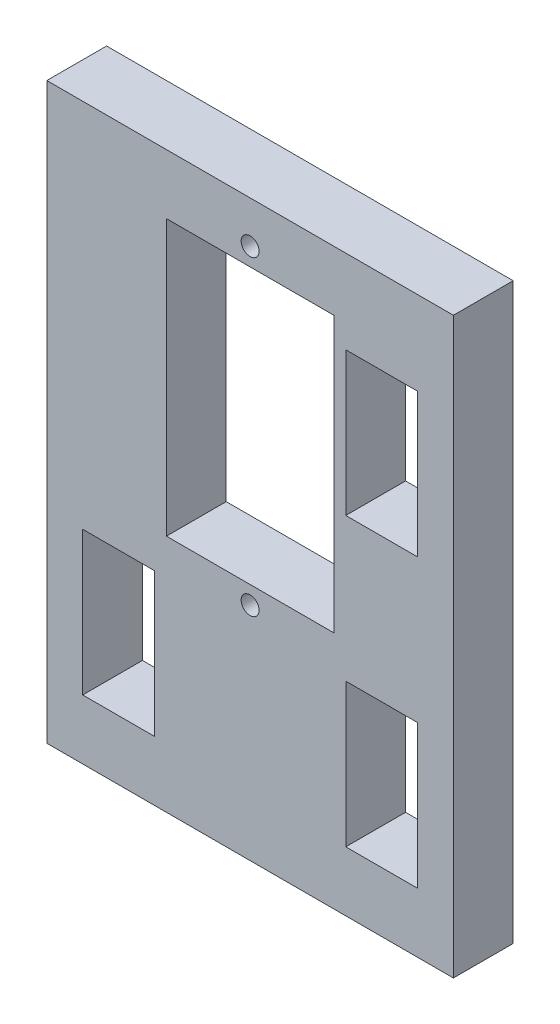
SolidWorks part; units mm, degrees
ref_plane "Alzado" through (0, 0, 0) normal (0, 0, 1) x (1, 0, 0)
ref_plane "Planta" through (0, 0, 0) normal (0, 1, 0) x (1, 0, 0)
ref_plane "Vista lateral" through (0, 0, 0) normal (1, 0, 0) x (0, 0, -1)
sketch "Croquis1" plane through (0, 0, 0) normal (0, 0, 1) x (1, 0, 0)
  line L0 (3, 48) -> (3, 0) construction
  line L1 (0, 0) -> (34, 0)
  line L2 (0, 0) -> (0, 48)
  line L3 (0, 48) -> (34, 48)
  line L4 (34, 0) -> (34, 48)
  line L5 (31, 48) -> (31, 0) construction
  line L6 (9, 48) -> (9, 0) construction
  line L7 (25, 48) -> (25, 0) construction
  line L8 (17, 48) -> (17, 0) construction
  line L10 (24, 20) -> (10, 20)
  line L11 (24, 20) -> (24, 43)
  line L12 (24, 43) -> (10, 43)
  line L13 (10, 20) -> (10, 43)
  line L14 (24, 20) -> (10, 43) construction
  line L15 (24, 43) -> (10, 20) construction
  line L16 (31, 5) -> (25, 5)
  line L17 (31, 5) -> (31, 17)
  line L18 (31, 17) -> (25, 17)
  line L19 (25, 5) -> (25, 17)
  line L20 (31, 29) -> (25, 29)
  line L21 (31, 29) -> (31, 41)
  line L22 (31, 41) -> (25, 41)
  line L23 (25, 29) -> (25, 41)
  line L24 (9, 5) -> (3, 5)
  line L25 (9, 5) -> (9, 17)
  line L26 (9, 17) -> (3, 17)
  line L27 (3, 5) -> (3, 17)
  circle A0 centre (17, 18.5) radius 0.75
  circle A1 centre (17, 44.5) radius 0.75
  point P15 (17, 31.5)
  point P36 (6, 5)
  dimension "D9" = 1.5
  dimension "D10" = 1.5
  dimension "D1" = 6
  dimension "D2" = 6
  dimension "D3" = 3
  dimension "D4" = 3
  dimension "D5" = 16
  dimension "D6" = 14
  dimension "D7" = 23
  dimension "D8" = 20
  dimension "D11" = 1.5
  dimension "D12" = 1.5
  dimension "D13" = 5
  dimension "D14" = 5
  dimension "D15" = 12
  dimension "D16" = 12
  dimension "D17" = 12
  dimension "D18" = 12
  dimension "D19" = 48
extrude "Saliente-Extruir1" add sketch "Croquis1" along normal blind 5
